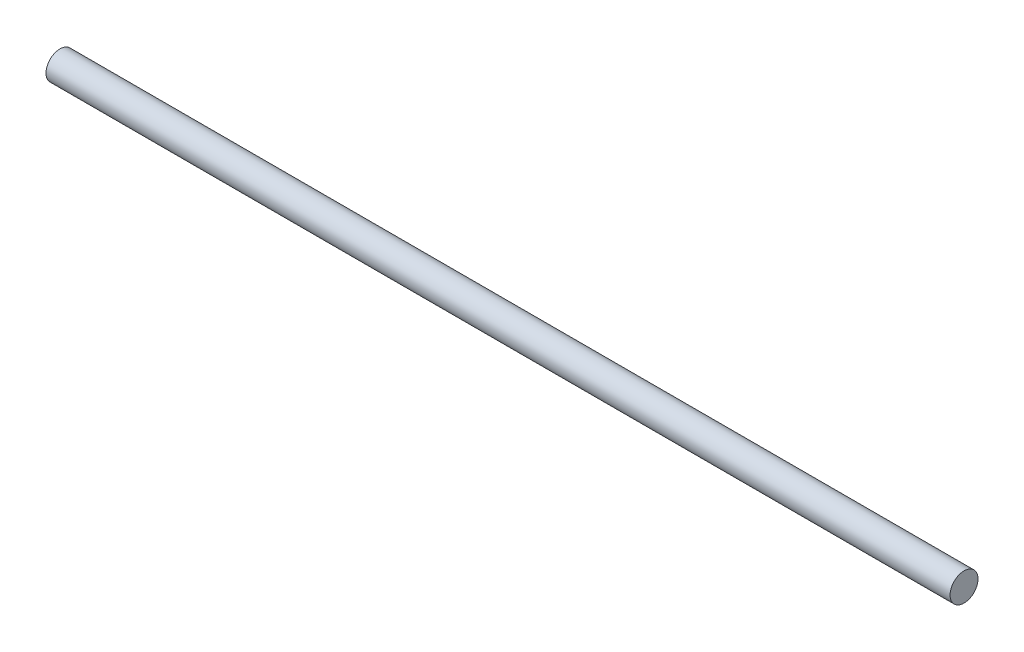
SolidWorks part; units mm, degrees
material "Stainless Steel (ferritic)"
ref_plane "Front Plane" through (0, 0, 0) normal (0, 0, 1) x (1, 0, 0)
ref_plane "Top Plane" through (0, 0, 0) normal (0, 1, 0) x (1, 0, 0)
ref_plane "Right Plane" through (0, 0, 0) normal (1, 0, 0) x (0, 0, -1)
sketch "Sketch1" plane through (0, 0, 0) normal (1, 0, 0) x (0, 0, -1)
  circle A0 centre (0, 0) radius 1.5
  dimension "D1" = 3
extrude "Boss-Extrude1" add sketch "Sketch1" along normal blind 97 contours A0
